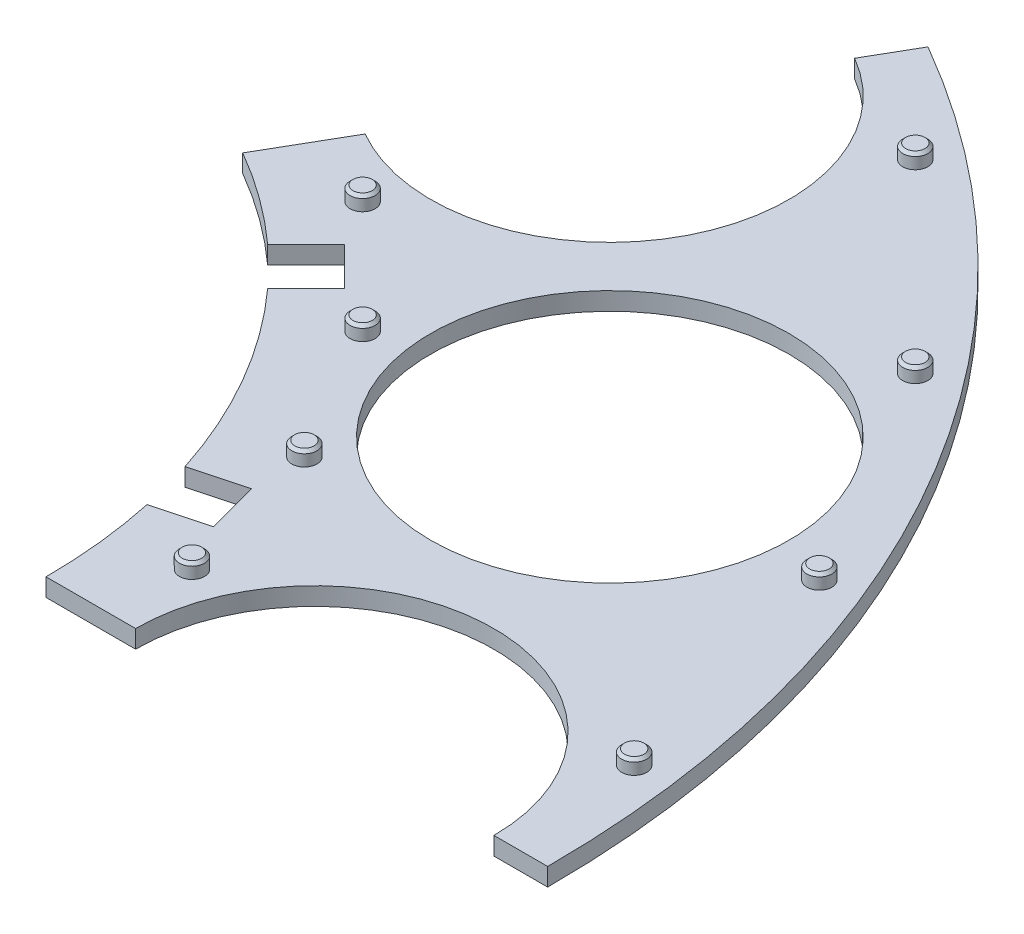
SolidWorks part; units mm, degrees
ref_plane "Ebene vorne" through (0, 0, 0) normal (0, 0, 1) x (1, 0, 0)
ref_plane "Ebene oben" through (0, 0, 0) normal (0, 1, 0) x (1, 0, 0)
ref_plane "Ebene rechts" through (0, 0, 0) normal (1, 0, 0) x (0, 0, -1)
sketch "Skizze1" plane through (0, 0, 0) normal (0, 1, 0) x (1, 0, 0)
  line L0 (150, 0) -> (290, 0)
  line L1 (145, 251.1474) -> (75, 129.9038)
  line L2 (0, 0) -> (290, 0) construction
  line L3 (0, 0) -> (145, 251.1474) construction
  arc A1 (150, 0) -> (75, 129.9038) centre (0, 0) ccw
  arc A2 (290, 0) -> (145, 251.1474) centre (0, 0) ccw
  dimension "D1" = 290
  dimension "D2" = 150
  dimension "D3" = 60
extrude "Aufsatz-Linear austragen1" add sketch "Skizze1" along normal blind 5
sketch "Skizze2" plane through (0, 5, 0) normal (0, 1, 0) x (1, 0, 0)
  line L0 (150, 0) -> (290, 0) construction
  line L1 (145, 251.1474) -> (75, 129.9038) construction
  line L2 (0, 0) -> (194.8557, 112.5) construction
  arc A1 (225, 0) -> (112.5, 194.8557) centre (0, 0) ccw construction
  circle A2 centre (112.5, 194.8557) radius 50
  circle A3 centre (194.8557, 112.5) radius 50
  circle A4 centre (225, 0) radius 50
  dimension "D1" = 225
  dimension "D2" = 100
extrude "Schnitt-Linear austragen1" cut sketch "Skizze2" against normal through all
sketch "Skizze3" plane through (0, 5, 0) normal (0, 1, 0) x (1, 0, 0)
  line L0 (0, 0) -> (287.519, 37.8526) construction
  line L1 (0, 0) -> (267.9251, 110.9782) construction
  line L2 (0, 0) -> (230.0725, 176.5408) construction
  line L3 (0, 0) -> (176.5408, 230.0725) construction
  line L4 (150, 0) -> (175, 0) construction
  line L6 (275, 0) -> (290, 0) construction
  line L7 (145, 251.1474) -> (137.5, 238.157) construction
  arc A0 (290, 0) -> (145, 251.1474) centre (0, 0) ccw construction
  arc A1 (170, 0) -> (85, 147.2243) centre (0, 0) ccw construction
  arc A2 (280, 0) -> (140, 242.4871) centre (0, 0) ccw construction
  circle A3 centre (168.5456, 22.1895) radius 3.5
  circle A4 centre (277.6046, 36.5473) radius 3.5
  circle A5 centre (157.0595, 65.0562) radius 3.5
  circle A6 centre (134.8701, 103.4894) radius 3.5
  circle A7 centre (103.4894, 134.8701) radius 3.5
  circle A8 centre (170.4532, 222.1389) radius 3.5
  circle A9 centre (222.1389, 170.4532) radius 3.5
  circle A10 centre (258.6863, 107.1514) radius 3.5
  dimension "D5" = 170
  dimension "D6" = 280
  dimension "D7" = 7
  dimension "D1" = 15
  dimension "D2" = 15
  dimension "D3" = 15
  dimension "D4" = 7.5
extrude "Aufsatz-Linear austragen2" add sketch "Skizze3" along normal blind 4
chamfer "Fase1" distance 0.8 angle 45 8 edges at (277.6046, 9, -33.0473) (157.0595, 9, -61.5562) (134.8701, 9, -99.9894) (170.4532, 9, -218.6389) (222.1389, 9, -166.9532) (258.6863, 9, -103.6514) (168.5456, 9, -18.6895) (103.4894, 9, -131.3701)
sketch "Skizze4" plane through (0, 5, 0) normal (0, 1, 0) x (1, 0, 0)
  line L0 (0, 0) -> (280.1185, 75.0575) construction
  line L1 (0, 0) -> (205.061, 205.061) construction
  line L2 (150, 0) -> (175, 0) construction
  line L3 (100.6301, 111.2367) -> (111.3693, 121.9759)
  line L4 (111.3693, 121.9759) -> (121.9759, 111.3693)
  line L5 (121.9759, 111.3693) -> (111.2367, 100.6301)
  line L6 (142.7665, 46.0187) -> (157.4366, 49.9496)
  line L7 (157.4366, 49.9496) -> (161.3189, 35.4607)
  line L8 (161.3189, 35.4607) -> (146.6488, 31.5299)
  line L9 (87.5, 151.5544) -> (75, 129.9038) construction
  arc A0 (290, 0) -> (145, 251.1474) centre (0, 0) ccw construction
  arc A1 (111.2367, 100.6301) -> (100.6301, 111.2367) centre (0, 0) ccw
  arc A2 (146.6488, 31.5299) -> (142.7665, 46.0187) centre (0, 0) ccw
  arc A3 (150, 0) -> (75, 129.9038) centre (0, 0) ccw construction
  arc A4 (165, 0) -> (82.5, 142.8942) centre (0, 0) ccw construction
  point P20 (116.6726, 116.6726)
  point P21 (159.3778, 42.7051)
  dimension "D3" = 165
  dimension "D1" = 15
  dimension "D2" = 30
  dimension "D4" = 15
extrude "Schnitt-Linear austragen2" cut sketch "Skizze4" against normal through all
